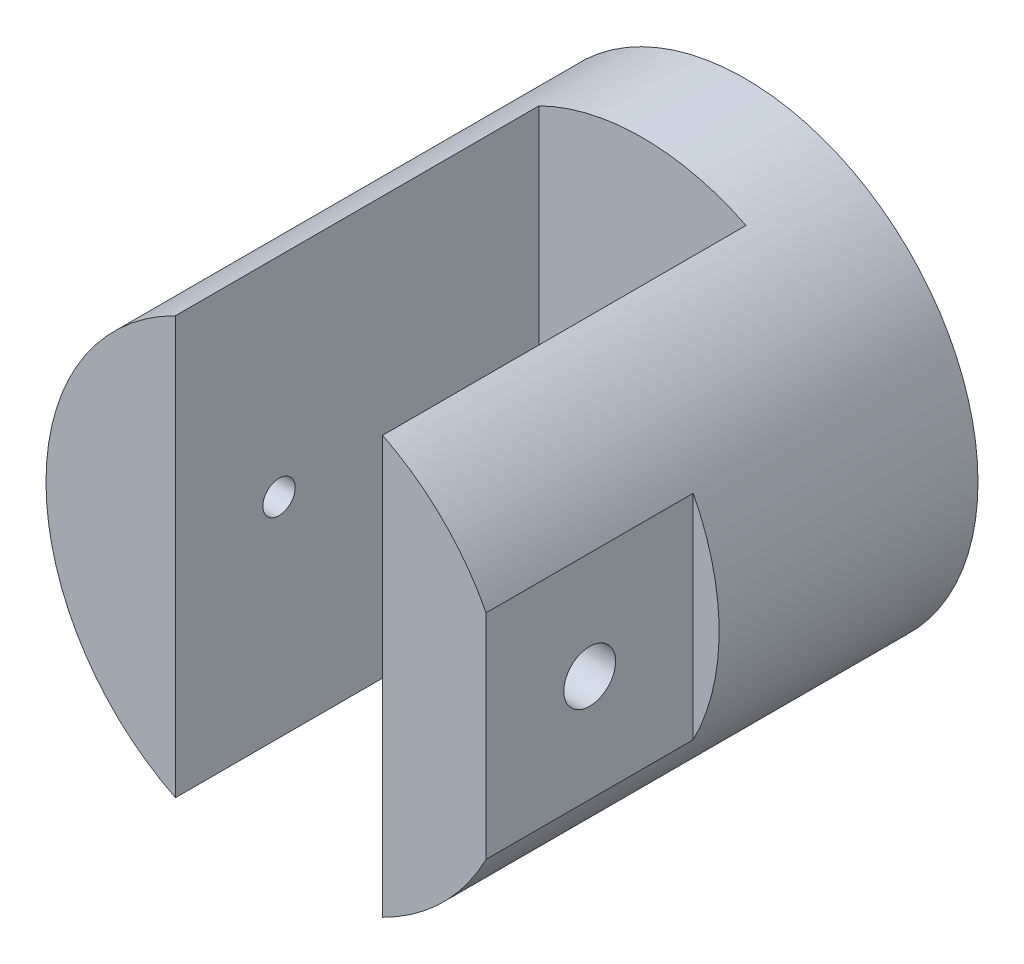
SolidWorks part; units mm, degrees
material "6061 Alloy"
ref_plane "Front Plane" through (0, 0, 0) normal (0, 0, 1) x (1, 0, 0)
ref_plane "Top Plane" through (0, 0, 0) normal (0, 1, 0) x (1, 0, 0)
ref_plane "Right Plane" through (0, 0, 0) normal (1, 0, 0) x (0, 0, -1)
sketch "Sketch1" plane through (0, 0, 0) normal (0, 0, 1) x (1, 0, 0)
  circle A0 centre (0, 0) radius 28.575
  dimension "D1" = 57.15
extrude "OD Don't Care" add sketch "Sketch1" along normal blind 57.15
sketch "Sketch3" plane through (0, 0, 0) normal (0, 1, 0) x (1, 0, 0)
  line L0 (-28.575, -57.15) -> (28.575, -57.15) construction
  line L1 (-12.7, -12.573) -> (12.7, -12.573)
  line L2 (-12.7, -12.573) -> (-12.7, -57.15)
  line L3 (-12.7, -57.15) -> (12.7, -57.15)
  line L4 (12.7, -12.573) -> (12.7, -57.15)
  line L5 (-12.7, -12.573) -> (12.7, -57.15) construction
  line L6 (-12.7, -57.15) -> (12.7, -12.573) construction
  line L7 (28.575, 0) -> (-28.575, 0) construction
  point P0 (0, -34.8615)
  dimension "D1" = 25.4
  dimension "D2" = 12.573
extrude "Slot" cut sketch "Sketch3" against normal mid plane 101.6
sketch "Sketch4" plane through (0, 0, 12.573) normal (0, 0, 1) x (1, 0, 0)
  circle A0 centre (0, 0) radius 7.9375
  dimension "D1" = 15.875
extrude "5/8\" Through Hole" cut sketch "Sketch4" against normal through all
sketch "Sketch5" plane through (0, 0, 57.15) normal (0, 0, 1) x (1, 0, 0)
  line L0 (-12.7, 0) -> (25.4, 0) construction
  line L1 (25.4, -25.5977) -> (-28.575, -25.5977)
  line L2 (25.4, -25.5977) -> (25.4, 25.5977)
  line L3 (25.4, 25.5977) -> (-28.575, 25.5977)
  line L4 (-28.575, -25.5977) -> (-28.575, 25.5977)
  line L5 (25.4, -25.5977) -> (-28.575, 25.5977) construction
  line L6 (25.4, 25.5977) -> (-28.575, -25.5977) construction
  line L7 (-12.7, -25.5977) -> (-12.7, 25.5977) construction
  arc A0 (-12.7, 25.5977) -> (-12.7, -25.5977) centre (0, 0) ccw construction
  point P0 (-1.5875, 0)
  dimension "D1" = 38.1
extrude "Flat Surface" cut sketch "Sketch5" against normal blind 25.4 flip side to cut
sketch "Sketch2" plane through (25.4, 0, 0) normal (1, 0, 0) x (0, 0, -1)
  line L0 (-57.15, 28.575) -> (-57.15, -28.575) construction
  circle A0 centre (-44.45, 0) radius 3.175
  dimension "D1" = 6.35
  dimension "D2" = 12.7
extrude "1/4\" Through Hole" cut sketch "Sketch2" against normal up to surface (38.1 mm away) up to face at (-12.7, 0, 34.8615)
sketch "Sketch7" plane through (-12.7, 0, 0) normal (1, 0, 0) x (0, 0, -1)
  circle A0 centre (-44.45, 0) radius 1.9844
  dimension "D4" = 3.9688
extrude "10-32 Threaded Hole" cut sketch "Sketch7" against normal through all
